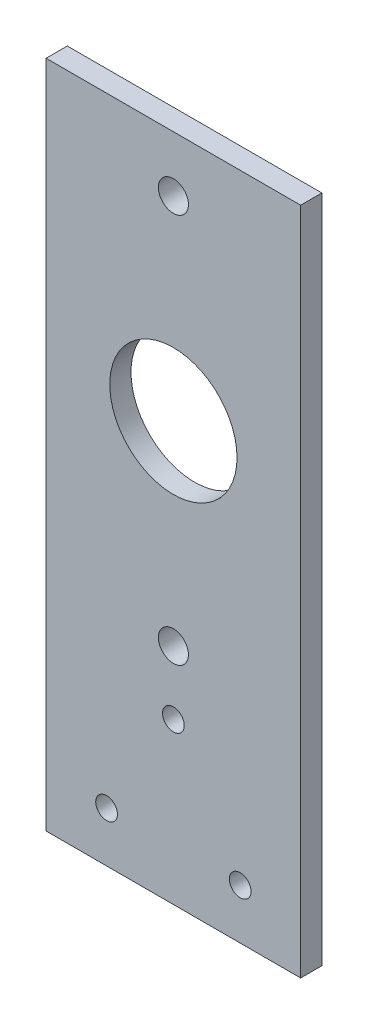
SolidWorks part; units mm, degrees
ref_plane "Front Plane" through (0, 0, 0) normal (0, 0, 1) x (1, 0, 0)
ref_plane "Top Plane" through (0, 0, 0) normal (0, 1, 0) x (1, 0, 0)
ref_plane "Right Plane" through (0, 0, 0) normal (1, 0, 0) x (0, 0, -1)
sketch "Sketch1" plane through (0, 0, 0) normal (0, 0, 1) x (1, 0, 0)
  line L0 (0, 0) -> (-80.1146, 0) construction
  line L1 (0, 0) -> (0, -87.0565) construction
  line L2 (-70.7055, -110.35) -> (63.6449, -110.35) construction
  line L3 (-38.1, 75) -> (38.1, 75)
  line L4 (-38.1, 75) -> (-38.1, -125.35)
  line L5 (-38.1, -125.35) -> (38.1, -125.35)
  line L6 (38.1, 75) -> (38.1, -125.35)
  circle A0 centre (0, 0) radius 19.05
  circle A1 centre (0, 58.34) radius 4.5
  circle A2 centre (0, -58.34) radius 4.5
  circle A3 centre (-20, -110.35) radius 3.25
  circle A4 centre (20, -110.35) radius 3.25
  circle A5 centre (0, -77.35) radius 3.25
  dimension "D1" = 38.1
  dimension "D2" = 9
  dimension "D3" = 9
  dimension "D9" = 6.5
  dimension "D10" = 6.5
  dimension "D12" = 6.5
  dimension "D4" = 116.68
  dimension "D5" = 76.2
  dimension "D6" = 75
  dimension "D7" = 125.35
  dimension "D8" = 15
  dimension "D11" = 40
  dimension "D13" = 33
extrude "Boss-Extrude1" add sketch "Sketch1" along normal blind 6.35
